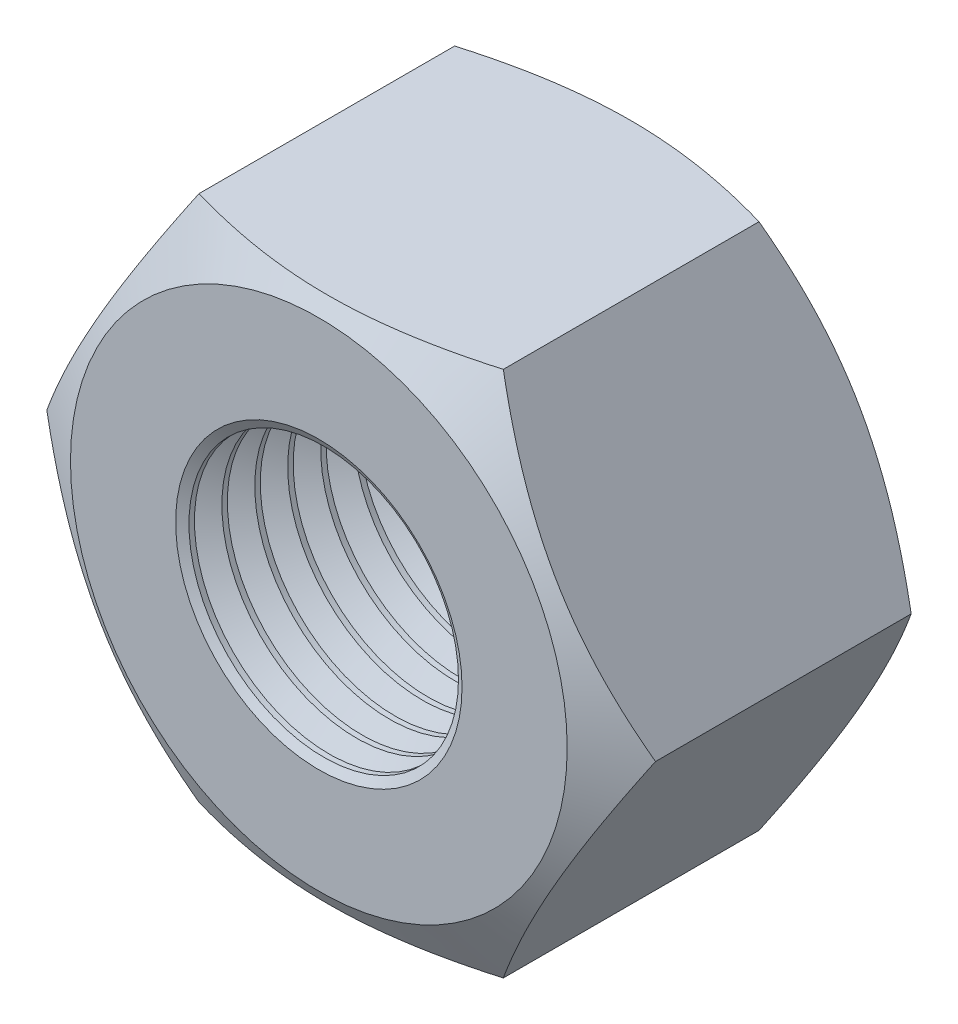
SolidWorks part; units mm, degrees
ref_plane "Front" through (0, 0, 0) normal (0, 0, 1) x (1, 0, 0)
ref_plane "Top" through (0, 0, 0) normal (0, 1, 0) x (1, 0, 0)
ref_plane "Right" through (0, 0, 0) normal (1, 0, 0) x (0, 0, -1)
sketch "Sketch1" plane through (0, 0, 0) normal (0, 0, 1) x (1, 0, 0)
  line L1 (3.7528, -6.5) -> (7.5056, 0)
  line L2 (7.5056, 0) -> (3.7528, 6.5)
  line L3 (3.7528, 6.5) -> (-3.7528, 6.5)
  line L4 (-3.7528, 6.5) -> (-7.5056, 0)
  line L5 (-7.5056, 0) -> (-3.7528, -6.5)
  line L6 (-3.7528, -6.5) -> (3.7528, -6.5)
  circle A0 centre (0, 0) radius 6.5 construction
  circle A1 centre (0, 0) radius 3.3235
  dimension "D" = 6.647
  dimension "s" = 13
extrude "BaseNut" add sketch "Sketch1" against normal blind 7.9
cosmetic thread "ThreadCosmetic1" [suppressed] parameters "D"=8
sketch "Sketch2" plane through (0, 0, 0) normal (0, 1, 0) x (1, 0, 0)
  line L0 (-7.5056, 7.9) -> (-6.125, 7.9)
  line L2 (-6.125, 7.9) -> (-7.5056, 7.1029)
  line L3 (-7.5056, 7.1029) -> (-7.5056, 7.9)
  line L4 (0, 3.3759) -> (0, -9.8171) construction
  line L6 (-9.7712, 3.95) -> (9.8853, 3.95) construction
  line L7 (-7.5056, 0.7971) -> (-7.5056, 0)
  line L8 (-6.125, 0) -> (-7.5056, 0.7971)
  line L9 (-7.5056, 0) -> (-6.125, 0)
  line L10 (-7.5056, 7.9) -> (-7.5056, 0) construction
  dimension "dw" = 12.25
  dimension "D1" = 30
  dimension "D2" = 3.95
revolve "Double-Chamfer" cut sketch "Sketch2" angle 360 about L4
sketch "Sketch4" plane through (0, 0, 0) normal (0, 1, 0) x (1, 0, 0)
  line L0 (3.9094, 7.9) -> (3.3235, 7.5618)
  line L1 (3.3235, 7.5618) -> (2.647, 7.5618)
  line L2 (2.647, 7.5618) -> (2.647, 8.2383)
  line L3 (2.647, 8.2383) -> (3.3235, 8.2383)
  line L4 (3.3235, 8.2383) -> (3.9094, 7.9)
  line L5 (0, 0) -> (0, 109.7681) construction
  dimension "D1" = 0.6765
  dimension "D2" = 6.647
revolve "Cut-Revolve10" cut sketch "Sketch4" angle 360 about L5
pattern_linear "LPattern10" count 11 spacing 0.8118 along (0, 0, 1) of "Cut-Revolve10"
equation "\"dw@Sketch2\" = \"s@Sketch1\"-0.75"
equation "\"D2@Sketch2\" = \"m@BaseNut\" / 2"
equation "\"D2@Sketch4\"=\"D@Sketch1\""
equation "\"D1@Sketch4\" =  (\"D@ThreadCosmetic1\" - \"D2@Sketch4\"  )  / 2"
equation "\"D3@LPattern10\" = \"D1@Sketch4\" * 1.2"
equation "\"D1@LPattern10\" = \"m@BaseNut\" / \"D3@LPattern10\" + 1"
